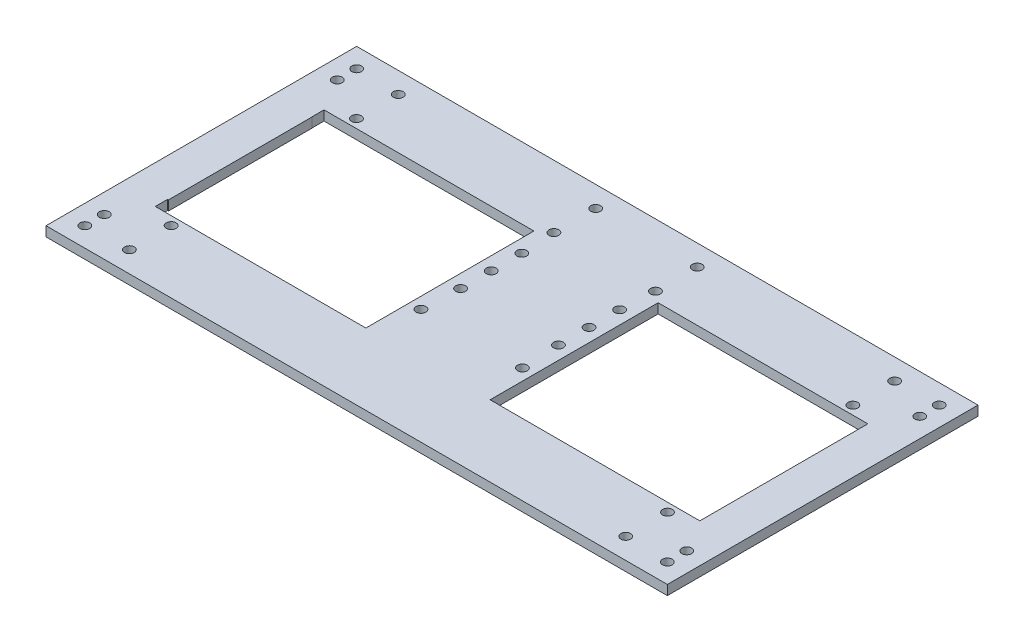
SolidWorks part; units mm, degrees
ref_plane "Front" through (0, 0, 0) normal (0, 0, 1) x (1, 0, 0)
ref_plane "Top" through (0, 0, 0) normal (0, 1, 0) x (1, 0, 0)
ref_plane "Right" through (0, 0, 0) normal (1, 0, 0) x (0, 0, -1)
sketch "Sketch1" plane through (0, 0, 0) normal (0, 1, 0) x (1, 0, 0)
  line L0 (0, -50.8) -> (203.2, -50.8)
  line L1 (0, 0) -> (203.2, 0)
  line L2 (0, 0) -> (0, -101.6)
  line L3 (0, -101.6) -> (203.2, -101.6)
  line L4 (203.2, 0) -> (203.2, -101.6)
  line L5 (101.6, 0) -> (0, 0)
  line L6 (50.8, 0) -> (50.8, -101.6)
  line L7 (101.6, 0) -> (203.2, 0)
  line L8 (152.4, 0) -> (152.4, -101.6)
  line L9 (12.7, -27.3231) -> (12.7, -74.2769)
  line L10 (81.28, -27.3231) -> (81.28, -74.2769)
  line L11 (12.7, -27.3231) -> (81.28, -27.3231)
  line L12 (12.7, -74.2769) -> (81.28, -74.2769)
  line L14 (121.92, -27.3231) -> (121.92, -74.2769)
  line L15 (101.6, 0) -> (101.6, -101.6)
  line L16 (12.7, 0) -> (12.7, -13.6616)
  line L17 (12.7, -13.6616) -> (12.7, -27.3231)
  line L18 (12.7, -74.2769) -> (12.7, -87.9384)
  line L19 (12.7, -87.9384) -> (12.7, -101.6)
  line L20 (190.5, -27.3231) -> (121.92, -27.3231)
  line L22 (190.5, -74.2769) -> (121.92, -74.2769)
  line L23 (190.5, -27.3231) -> (121.92, -27.3231)
  line L31 (121.92, -27.3231) -> (121.92, -23.3231)
  line L32 (190.5, -23.3231) -> (121.92, -23.3231)
  line L33 (190.5, -74.2769) -> (121.92, -74.2769)
  line L34 (190.5, -74.2769) -> (190.5, -78.2769)
  line L35 (121.92, -74.2769) -> (121.92, -78.2769)
  line L36 (190.5, -78.2769) -> (121.92, -78.2769)
  line L37 (81.28, -74.2769) -> (81.28, -78.2769)
  line L38 (81.28, -74.2769) -> (12.4051, -74.2769)
  line L39 (81.28, -78.2769) -> (12.4051, -78.2769)
  line L40 (12.4051, -74.2769) -> (12.4051, -78.2769)
  line L41 (81.28, -27.3231) -> (81.28, -23.3231)
  line L42 (81.28, -27.3231) -> (12.6484, -27.3231)
  line L43 (81.28, -23.3231) -> (12.6484, -23.3231)
  line L44 (12.6484, -27.3231) -> (12.6484, -23.3231)
  line L45 (118.2, -6.8308) -> (118.2, -20.4924)
  line L46 (190.5, -23.3231) -> (190.5, -27.3231)
  line L47 (190.5, -74.2769) -> (190.5, -27.3231)
  line L48 (117.6, -51.6) -> (85.6, -51.6)
  line L49 (117.6, -51.6) -> (117.6, -41.6)
  line L50 (117.6, -41.6) -> (117.6, -31.6)
  line L51 (117.6, -41.6) -> (85.6, -41.6)
  line L52 (117.6, -31.6) -> (85.6, -31.6)
  circle A0 centre (12.7, -6.8308) radius 1.6
  circle A1 centre (12.7, -81.1076) radius 1.6
  circle A2 centre (12.7, -94.7692) radius 1.6
  circle A3 centre (12.7, -20.4924) radius 1.6
  circle A4 centre (190.5, -94.7692) radius 1.6
  circle A5 centre (190.5, -81.1076) radius 1.6
  circle A6 centre (190.5, -6.8308) radius 1.6
  circle A7 centre (190.5, -20.4924) radius 1.6
  circle A8 centre (118.2, -6.8308) radius 1.6
  circle A15 centre (85, -6.8308) radius 1.6
  circle A20 centre (118.2, -20.4924) radius 1.6
  circle A23 centre (85, -20.4924) radius 1.6
  circle A24 centre (182.769, -6.8308) radius 1.6
  circle A25 centre (182.769, -20.4924) radius 1.6
  circle A26 centre (182.769, -94.7692) radius 1.6
  circle A27 centre (182.769, -81.1076) radius 1.6
  circle A28 centre (20.431, -94.7692) radius 1.6
  circle A29 centre (20.431, -81.1076) radius 1.6
  circle A30 centre (20.431, -20.4924) radius 1.6
  circle A31 centre (20.431, -6.8308) radius 1.6
  circle A32 centre (85, -63.9814) radius 1.6
  circle A33 centre (118.2, -63.9814) radius 1.6
  circle A34 centre (117.6, -51.6) radius 1.6
  circle A35 centre (85.6, -51.6) radius 1.6
  circle A36 centre (117.6, -41.6) radius 1.6
  circle A37 centre (117.6, -31.6) radius 1.6
  circle A38 centre (85.6, -31.6) radius 1.6
  circle A39 centre (85.6, -41.6) radius 1.6
  point P15 (12.7, -50.8)
  point P16 (12.7, -50.8)
  point P19 (81.28, -50.8)
  point P60 (101.6, -50.8)
  point P66 (101.6, -51.6)
  dimension "D5" = 32
  dimension "D7" = 46.9537
  dimension "D11" = 43.489
  dimension "D13" = 10
  dimension "D1" = 101.6
  dimension "D2" = 203.2
  dimension "D3" = 30.48
  dimension "D4" = 38.1
  dimension "D6" = 0
  dimension "D8" = 4
  dimension "D9" = 4
  dimension "D10" = 85
  dimension "D12" = 13.6616
  dimension "D14" = 10
  dimension "D15" = 50
  dimension "D16" = 0
extrude "Boss-Extrude1" add sketch "Sketch1" against normal blind 3.175
sketch "Sketch2" plane through (0, -3.175, 0) normal (0, -1, 0) x (1, 0, 0)
  line L0 (101.6, 0) -> (101.6, 101.6)
  line L1 (0, 0) -> (203.2, 0) construction
  line L2 (0, 101.6) -> (203.2, 101.6) construction
  line L3 (196.85, 50.8) -> (6.35, 50.8)
  line L4 (6.35, 12.7) -> (6.35, 88.9)
  line L5 (196.85, 12.7) -> (196.85, 88.9)
  line L6 (196.85, 12.7) -> (196.85, 6.35)
  line L7 (6.35, 88.9) -> (6.35, 95.25)
  circle A0 centre (196.85, 12.7) radius 1.6
  circle A1 centre (196.85, 88.9) radius 1.6
  circle A2 centre (6.35, 88.9) radius 1.6
  circle A3 centre (6.35, 12.7) radius 1.6
  circle A4 centre (196.85, 6.35) radius 1.6
  circle A5 centre (6.35, 6.35) radius 1.6
  circle A6 centre (6.35, 95.25) radius 1.6
  circle A7 centre (196.85, 95.25) radius 1.6
  point P9 (101.6, 50.8)
  point P12 (6.35, 50.8)
  point P15 (196.85, 50.8)
  dimension "D1" = 190.5
  dimension "D5" = 6.35
  dimension "D2" = 76.2
  dimension "D3" = 76.2
  dimension "D4" = 6.35
extrude "Cut-Extrude1" cut sketch "Sketch2" against normal blind 10
